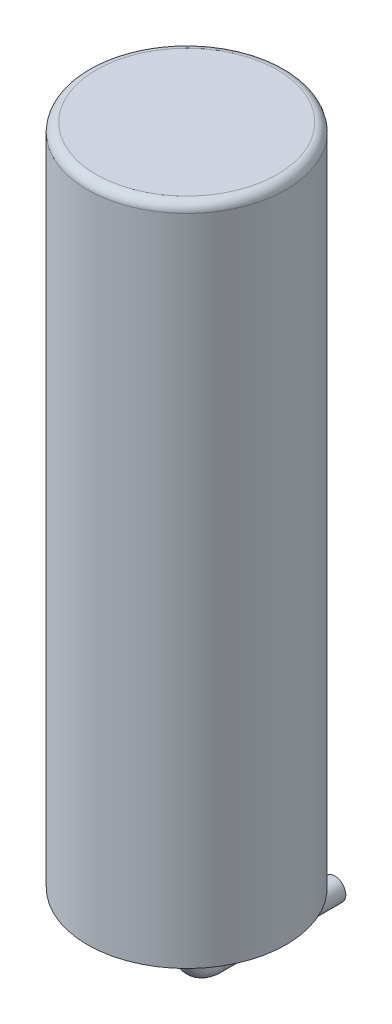
SolidWorks part; units mm, degrees
ref_plane "Front Plane" through (0, 0, 0) normal (0, 0, 1) x (1, 0, 0)
ref_plane "Top Plane" through (0, 0, 0) normal (0, 1, 0) x (1, 0, 0)
ref_plane "Right Plane" through (0, 0, 0) normal (1, 0, 0) x (0, 0, -1)
sketch "Sketch1" plane through (0, 0, 0) normal (0, 1, 0) x (1, 0, 0)
  circle A0 centre (0, 0) radius 2.25
  dimension "D1" = 4.5
extrude "Boss-Extrude1" add sketch "Sketch1" along normal blind 15
sketch "Sketch2" plane through (0, 0, 0) normal (0, -1, 0) x (1, 0, 0)
  circle A0 centre (0, 0) radius 0.25
  dimension "D1" = 0.5
sketch "Sketch3" plane through (0, 0, 0) normal (1, 0, 0) x (0, 0, -1)
  line L0 (0, 0) -> (0, -1.1)
  line L1 (0.6, -1.7) -> (3.35, -1.7)
  arc A0 (0, -1.1) -> (0.6, -1.7) centre (0.6, -1.1) ccw
  dimension "D1" = 0.6
  dimension "D2" = 2.75
  dimension "D3" = 1.1
sweep "Sweep1" add profiles "Sketch2" path "Sketch3"
sketch "Sketch4" plane through (0, 0, 0) normal (0, -1, 0) x (1, 0, 0)
  circle A0 centre (-1.125, 0) radius 0.1
  dimension "D1" = 0.2
  dimension "D2" = 1.125
sketch "Sketch5" plane through (0, 0, 0) normal (1, 0, 0) x (0, 0, -1)
  line L0 (0, 0) -> (0, -1.1)
  line L1 (0.6, -1.7) -> (1.1, -1.7)
  arc A0 (0, -1.1) -> (0.6, -1.7) centre (0.6, -1.1) ccw
  dimension "D1" = 0.6
  dimension "D2" = 0.5
  dimension "D3" = 1.1
sweep "Sweep2" add profiles "Sketch4" path "Sketch5"
fillet "Fillet1" radius 0.2 1 edges at (0, 15, 2.25)
